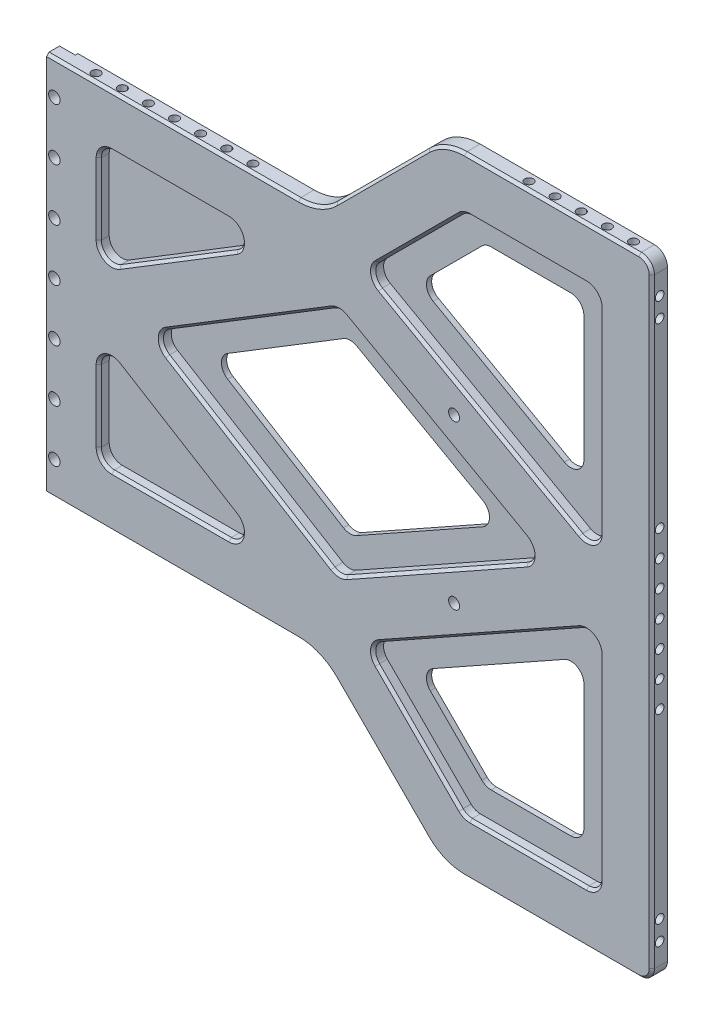
SolidWorks part; units mm, degrees
material "7075-T6 (SN)"
ref_plane "前视基准面" through (0, 0, 0) normal (0, 0, 1) x (1, 0, 0)
ref_plane "上视基准面" through (0, 0, 0) normal (0, 1, 0) x (1, 0, 0)
ref_plane "右视基准面" through (0, 0, 0) normal (1, 0, 0) x (0, 0, -1)
sketch "草图1" plane through (0, 0, 0) normal (0, 0, 1) x (1, 0, 0)
  line L0 (11.5, -73) -> (-13.5, -73) construction
  line L1 (11.5, 73) -> (110.1759, 73)
  line L2 (11.5, 73) -> (11.5, -73)
  line L3 (11.5, -73) -> (110.1759, -73)
  line L5 (387.1759, 0) -> (237.1759, 0) construction
  line L6 (-812.8241, 0) -> (387.1759, 0) construction
  line L7 (237.1759, 120) -> (237.1759, -120)
  line L8 (237.1759, 120) -> (157.1759, 120)
  line L11 (237.1759, -120) -> (157.1759, -120)
  line L12 (157.1759, 120) -> (110.1759, 73)
  line L13 (157.1759, -120) -> (110.1759, -73)
  point P10 (237.1759, 0)
  point P15 (237.1759, 0)
extrude "凸台-拉伸1" add sketch "草图1" against normal blind 1
sketch "草图2" plane through (0, 0, 0) normal (0, 0, 1) x (1, 0, 0)
  line L0 (11.5, 73) -> (5.5, 73)
  line L1 (5.5, 73) -> (5.5, -73)
  line L2 (5.5, -73) -> (11.5, -73)
  line L8 (11.5, 73) -> (11.5, -73)
  line L9 (11.5, -73) -> (110.1759, -73)
  line L10 (110.1759, -73) -> (157.1759, -120)
  line L11 (157.1759, -120) -> (237.1759, -120)
  line L12 (237.1759, -120) -> (237.1759, 120)
  line L13 (237.1759, 120) -> (157.1759, 120)
  line L14 (157.1759, 120) -> (110.1759, 73)
  line L15 (110.1759, 73) -> (11.5, 73)
  line L16 (11.5, 73) -> (11.5, -73) construction
  line L17 (11.5, -73) -> (110.1759, -73)
  line L18 (110.1759, -73) -> (157.1759, -120)
  line L19 (157.1759, -120) -> (237.1759, -120)
  line L20 (237.1759, -120) -> (237.1759, 120)
  line L21 (237.1759, 120) -> (157.1759, 120)
  line L22 (157.1759, 120) -> (110.1759, 73)
  line L23 (110.1759, 73) -> (11.5, 73)
  dimension "D1" = 0
extrude "凸台-拉伸2" add sketch "草图2" along normal blind 5
fillet "圆角1" radius 20 4 edges at (157.1759, 120, 2) (157.1759, -120, 2) (110.1759, -73, 2) (110.1759, 73, 2)
sketch "草图3" plane through (0, 0, 5) normal (0, 0, 1) x (1, 0, 0)
  line L8 (217.1759, 0) -> (117.1989, 56.0448) construction
  line L9 (217.1759, 0) -> (117.1989, -56.0448) construction
  line L11 (25.5, 0) -> (117.1989, 56.0448) construction
  line L12 (25.5, 0) -> (117.1989, -56.0448) construction
  line L13 (237.6263, 0) -> (116.9806, 67.6312)
  line L14 (6.3243, 0) -> (116.9806, 67.6312)
  line L15 (6.3243, 0) -> (116.9806, -67.6312)
  line L16 (217.1759, 100) -> (165.4601, 100)
  line L17 (165.4601, 100) -> (130.1759, 64.7157)
  line L18 (101.8916, 53) -> (25.5, 53)
  line L19 (25.5, 53) -> (25.5, -53)
  line L20 (25.5, -53) -> (101.8916, -53)
  line L21 (130.1759, -64.7157) -> (165.4601, -100)
  line L22 (165.4601, -100) -> (217.1759, -100)
  line L23 (217.1759, -100) -> (217.1759, 100)
  line L24 (217.1759, 100) -> (165.4601, 100)
  line L25 (165.4601, 100) -> (130.1759, 64.7157)
  line L26 (101.8916, 53) -> (25.5, 53)
  line L27 (25.5, 53) -> (25.5, -53)
  line L28 (25.5, -53) -> (101.8916, -53)
  line L29 (130.1759, -64.7157) -> (165.4601, -100)
  line L30 (165.4601, -100) -> (217.1759, -100)
  line L31 (217.1759, -100) -> (217.1759, 100)
  line L32 (237.6263, 0) -> (116.9806, -67.6312)
  line L33 (196.7254, 0) -> (117.4172, 44.4584)
  line L34 (44.6757, 0) -> (117.4172, 44.4584)
  line L35 (44.6757, 0) -> (117.4172, -44.4584)
  line L36 (196.7254, 0) -> (117.4172, -44.4584)
  arc A8 (101.8916, 53) -> (130.1759, 64.7157) centre (101.8916, 93) ccw
  arc A9 (130.1759, -64.7157) -> (101.8916, -53) centre (101.8916, -93) ccw
  arc A10 (101.8916, 53) -> (130.1759, 64.7157) centre (101.8916, 93) ccw
  arc A11 (130.1759, -64.7157) -> (101.8916, -53) centre (101.8916, -93) ccw
  dimension "D2" = 10
  dimension "D1" = 20
  dimension "D3" = 10
extrude "切除-拉伸1" cut sketch "草图3" against normal blind 4 contours L36 L33 L34 L35 | A10 L13 L31 L24 L25 | A11 L29 L30 L31 L32 | L27 L28 L15 | L26 L27 L14
fillet "圆角2" radius 5 18 edges at (165.4601, -100, 3) (217.1759, -100, 3) (217.1759, -11.4641, 3) (127.1113, -61.9522, 3) (217.1759, 11.4641, 3) (165.4601, 100, 3) (127.1113, 61.9522, 3) (117.4172, 44.4584, 3) (44.6757, 0, 3) (117.4172, -44.4584, 3) (196.7254, 0, 3) (25.5, -53, 3) (93.0414, -53, 3) (25.5, -11.7198, 3) (25.5, 53, 3) (25.5, 11.7198, 3) (93.0414, 53, 3) (217.1759, 100, 3)
sketch "草图4" plane through (0, 0, 1) normal (0, 0, 1) x (1, 0, 0)
  line L8 (176.275, 0) -> (117.6355, 32.872)
  line L9 (117.6355, 32.872) -> (63.8513, 0)
  line L10 (63.8513, 0) -> (117.6355, -32.872)
  line L11 (117.6355, -32.872) -> (176.275, 0)
  line L12 (176.275, 0) -> (117.6355, 32.872)
  line L13 (117.6355, 32.872) -> (63.8513, 0)
  line L14 (63.8513, 0) -> (117.6355, -32.872)
  line L15 (117.6355, -32.872) -> (176.275, 0)
  line L19 (143.7124, 64.1101) -> (207.1759, 28.5339)
  line L20 (207.1759, 28.5339) -> (207.1759, 90)
  line L21 (207.1759, 90) -> (169.6023, 90)
  line L22 (169.6023, 90) -> (143.7124, 64.1101)
  line L23 (143.7124, 64.1101) -> (207.1759, 28.5339)
  line L24 (207.1759, 28.5339) -> (207.1759, 90)
  line L25 (207.1759, 90) -> (169.6023, 90)
  line L26 (169.6023, 90) -> (143.7124, 64.1101)
  line L31 (143.7124, -64.1101) -> (169.6023, -90)
  line L32 (169.6023, -90) -> (207.1759, -90)
  line L33 (207.1759, -90) -> (207.1759, -28.5339)
  line L34 (207.1759, -28.5339) -> (143.7124, -64.1101)
  line L35 (143.7124, -64.1101) -> (169.6023, -90)
  line L36 (169.6023, -90) -> (207.1759, -90)
  line L37 (207.1759, -90) -> (207.1759, -28.5339)
  line L38 (207.1759, -28.5339) -> (143.7124, -64.1101)
  dimension "D1" = 10
  dimension "D2" = 10
  dimension "D3" = 10
extrude "切除-拉伸2" cut sketch "草图4" against normal blind 5
fillet "圆角3" radius 5 12 edges at (63.8513, 0, 0) (117.6355, 32.872, 0) (176.275, 0, 0) (117.6355, -32.872, 0) (207.1759, 90, 0) (207.1759, 28.5339, 0) (169.6023, 90, 0) (207.1759, -90, 0) (169.6023, -90, 0) (143.7124, -64.1101, 0) (207.1759, -28.5339, 0) (143.7124, 64.1101, 0)
fillet "圆角4" radius 5 2 edges at (237.1759, 120, 2) (237.1759, -120, 2)
chamfer "倒角1" distance 1 angle 45 36 edges at (26.9645, 51.5355, 5) (25.5, 34.3178, 5) (52.8864, 53, 5) (28.0543, 16.2746, 5) (80.0858, 49.3544, 5) (55.4938, 30.0516, 5) (26.9645, -51.5355, 5) (25.5, -34.3178, 5) (52.8864, -53, 5) (28.0543, -16.2746, 5) (80.0858, -49.3544, 5) (55.4938, -30.0516, 5) (49.2635, 0, 5) (83.2874, 23.5989, 5) (83.2874, -23.5989, 5) (117.4322, 43.6643, 5) (117.4322, -43.6643, 5) (154.4582, 23.694, 5) (154.4582, -23.694, 5) (191.5002, 0, 5) (165.6178, -99.6194, 5) (147.9842, -82.5241, 5) (189.8535, -100, 5) (130.5553, -62.2931, 5) (215.7114, -98.5355, 5) (171.3971, -37.1266, 5) (217.1759, -57.4995, 5) (214.7032, -15.6848, 5) (171.3971, 37.1266, 5) (214.7032, 15.6848, 5) (130.5553, 62.2931, 5) (217.1759, 57.4995, 5) (147.9842, 82.5241, 5) (215.7114, 98.5355, 5) (165.6178, 99.6194, 5) (189.8535, 100, 5)
chamfer "倒角2" distance 1 angle 45 13 edges at (53.6958, 73, 5) (109.5453, 74.5224, 5) (133.6759, 96.5, 5) (53.6958, -73, 5) (157.8065, 118.4776, 5) (109.5453, -74.5224, 5) (198.818, 120, 5) (133.6759, -96.5, 5) (235.7114, 118.5355, 5) (157.8065, -118.4776, 5) (237.1759, 0, 5) (198.818, -120, 5) (235.7114, -118.5355, 5)
sketch "草图5" plane through (0, 0, 5) normal (0, 0, 1) x (1, 0, 0)
  circle A0 centre (8.5, 60) radius 2.2
  circle A1 centre (8.5, 40) radius 2.2
  circle A2 centre (8.5, 20) radius 2.2
  circle A3 centre (8.5, 0) radius 2.2
  circle A4 centre (8.5, -20) radius 2.2
  circle A5 centre (8.5, -40) radius 2.2
  circle A6 centre (8.5, -60) radius 2.2
  point P0 (8.5, 60)
  point P1 (8.5, 40)
  point P3 (8.5, 20)
  point P5 (8.5, 0)
  point P7 (8.5, -20)
  point P9 (8.5, -40)
  point P11 (8.5, -60)
  dimension "D1" = 7
extrude "切除-拉伸3" cut sketch "草图5" against normal through all both and the other way through all
hole_wizard "M4 螺纹孔1" positions "草图7" profile "草图8" tap size "M4" standard "GB"
sketch "草图7" plane through (0, -73, 0) normal (0, -1, 0) x (-1, 0, 0)
  point P0 (-81.5, -2)
  point P3 (-71.5, -2)
  point P6 (-61.5, -2)
  point P9 (-51.5, -2)
  point P12 (-41.5, -2)
  point P15 (-31.5, -2)
  point P18 (-21.5, -2)
sketch "草图8" plane through (81.5, -73, 2) normal (1, 0, 0) x (0, 0, -1)
  line L0 (0, 0) -> (0, 11.0914)
  line L1 (0, 11.0914) -> (1.65, 10.1)
  line L2 (1.65, 10.1) -> (1.65, 0)
  line L5 (1.65, 0) -> (0, 0)
  line L10 (0, 11.0914) -> (-1.65, 10.1) construction
  line L11 (0, -6.35) -> (0, 107.95) construction
  dimension "螺纹孔钻头直径" = 3.3
  dimension "螺纹孔钻头深度" = 10.1
  dimension "导头角度" = 118
cosmetic thread "孔螺蚊线1" parameters "D1"=8, "D2"=4
cosmetic thread "孔螺蚊线2" parameters "D1"=8, "D2"=4
cosmetic thread "孔螺蚊线3" parameters "D1"=8, "D2"=4
cosmetic thread "孔螺蚊线4" parameters "D1"=8, "D2"=4
cosmetic thread "孔螺蚊线5" parameters "D1"=8, "D2"=4
cosmetic thread "孔螺蚊线6" parameters "D1"=8, "D2"=4
cosmetic thread "孔螺蚊线7" parameters "D1"=8, "D2"=4
mirror "镜向1" about plane through (0, 0, 0) normal (0, 1, 0) of "M4 螺纹孔1"
cosmetic thread "孔螺蚊线8" parameters "D1"=8, "D2"=4
cosmetic thread "孔螺蚊线9" parameters "D1"=8, "D2"=4
cosmetic thread "孔螺蚊线10" parameters "D1"=8, "D2"=4
cosmetic thread "孔螺蚊线11" parameters "D1"=8, "D2"=4
cosmetic thread "孔螺蚊线12" parameters "D1"=8, "D2"=4
cosmetic thread "孔螺蚊线13" parameters "D1"=8, "D2"=4
cosmetic thread "孔螺蚊线14" parameters "D1"=8, "D2"=4
hole_wizard "M4 螺纹孔2" positions "草图10" profile "草图11" tap size "M4" standard "GB"
sketch "草图10" plane through (0, -120, 0) normal (0, -1, 0) x (-1, 0, 0)
  point P0 (-227.1759, -2)
  point P3 (-217.1759, -2)
  point P6 (-207.1759, -2)
  point P9 (-197.1759, -2)
  point P12 (-187.1759, -2)
sketch "草图11" plane through (227.1759, -120, 2) normal (1, 0, 0) x (0, 0, -1)
  line L0 (0, 0) -> (0, 11.0914)
  line L1 (0, 11.0914) -> (1.65, 10.1)
  line L2 (1.65, 10.1) -> (1.65, 0)
  line L5 (1.65, 0) -> (0, 0)
  line L10 (0, 11.0914) -> (-1.65, 10.1) construction
  line L11 (0, -6.35) -> (0, 107.95) construction
  dimension "螺纹孔钻头直径" = 3.3
  dimension "螺纹孔钻头深度" = 10.1
  dimension "导头角度" = 118
cosmetic thread "孔螺蚊线15" parameters "D1"=8, "D2"=4
cosmetic thread "孔螺蚊线16" parameters "D1"=8, "D2"=4
cosmetic thread "孔螺蚊线17" parameters "D1"=8, "D2"=4
cosmetic thread "孔螺蚊线18" parameters "D1"=8, "D2"=4
cosmetic thread "孔螺蚊线19" parameters "D1"=8, "D2"=4
mirror "镜向2" about plane through (0, 0, 0) normal (0, 1, 0) of "M4 螺纹孔2"
cosmetic thread "孔螺蚊线20" parameters "D1"=8, "D2"=4
cosmetic thread "孔螺蚊线21" parameters "D1"=8, "D2"=4
cosmetic thread "孔螺蚊线22" parameters "D1"=8, "D2"=4
cosmetic thread "孔螺蚊线23" parameters "D1"=8, "D2"=4
cosmetic thread "孔螺蚊线24" parameters "D1"=8, "D2"=4
hole_wizard "M4 螺纹孔3" positions "草图13" profile "草图14" tap size "M4" standard "GB"
sketch "草图13" plane through (237.1759, 0, 0) normal (1, 0, 0) x (0, 0, -1)
  point P0 (-2, -99.5)
  point P3 (-2, -107)
sketch "草图14" plane through (237.1759, -99.5, 2) normal (0, 1, 0) x (0, 0, -1)
  line L0 (0, 0) -> (0, 11.0914)
  line L1 (0, 11.0914) -> (1.65, 10.1)
  line L2 (1.65, 10.1) -> (1.65, 0)
  line L5 (1.65, 0) -> (0, 0)
  line L10 (0, 11.0914) -> (-1.65, 10.1) construction
  line L11 (0, -6.35) -> (0, 107.95) construction
  dimension "螺纹孔钻头直径" = 3.3
  dimension "螺纹孔钻头深度" = 10.1
  dimension "导头角度" = 118
cosmetic thread "孔螺蚊线26" parameters "D1"=8, "D2"=4
cosmetic thread "孔螺蚊线27" parameters "D1"=8, "D2"=4
mirror "镜向3" about plane through (0, 0, 0) normal (0, 1, 0) of "M4 螺纹孔3"
cosmetic thread "孔螺蚊线28" parameters "D1"=8, "D2"=4
cosmetic thread "孔螺蚊线29" parameters "D1"=8, "D2"=4
sketch "草图15" plane through (0, 0, 5) normal (0, 0, 1) x (1, 0, 0)
  line L0 (151.5, 0) -> (161.5, 0) construction
  line L1 (151.5, 70) -> (151.5, -70) construction
  line L2 (-812.8241, 0) -> (387.1759, 0) construction
  line L3 (133.4954, -36.5917) -> (142.2972, -52.293) construction
  line L4 (189.4341, -5.2337) -> (120.4603, -43.8989) construction
  line L5 (132.5744, -57.7433) -> (209.2419, -14.7652) construction
  line L6 (89.7964, -71.4061) -> (185.9962, -17.4786) construction
  line L7 (161.5, 31.2106) -> (161.5, -31.2106) construction
  point P15 (137.8963, -44.4423)
  point P18 (161.5, 0)
hole_wizard "M5 螺纹孔1" positions "草图16" profile "草图17" tap size "M5" standard "GB"
sketch "草图16" plane through (0, 0, 5) normal (0, 0, 1) x (1, 0, 0)
  point P0 (161.5, 31.2106)
  point P3 (161.5, -31.2106)
sketch "草图17" plane through (161.5, 31.2106, 5) normal (1, 0, 0) x (0, -1, 0)
  line L0 (0, 0) -> (0, 13.6618)
  line L1 (0, 13.6618) -> (2.1, 12.4)
  line L2 (2.1, 12.4) -> (2.1, 0)
  line L5 (2.1, 0) -> (0, 0)
  line L10 (0, 13.6618) -> (-2.1, 12.4) construction
  line L11 (0, -6.35) -> (0, 107.95) construction
  dimension "螺纹孔钻头直径" = 4.2
  dimension "螺纹孔钻头深度" = 12.4
  dimension "导头角度" = 118
cosmetic thread "孔螺蚊线30" parameters "D1"=10, "D2"=5
cosmetic thread "孔螺蚊线31" parameters "D1"=10, "D2"=5
sketch "草图18" plane through (237.1759, 0, 0) normal (1, 0, 0) x (0, 0, -1)
  line L0 (1, 0) -> (-5, 0) construction
  line L1 (1, -115) -> (1, 115) construction
  line L2 (-2, 10) -> (-2, -10) construction
  line L3 (-2, 20) -> (-2, -20) construction
  line L4 (-2, 30) -> (-2, -30) construction
  point P8 (-2, 0)
  point P12 (-2, 0)
  point P15 (-2, 0)
hole_wizard "M4 螺纹孔4" positions "草图19" profile "草图20" tap size "M4" standard "GB"
sketch "草图19" plane through (237.1759, 0, 0) normal (1, 0, 0) x (0, 0, -1)
  line L0 (-2, 10) -> (-2, -10) construction
  point P0 (-2, 30)
  point P3 (-2, 20)
  point P6 (-2, 10)
  point P9 (-2, 0)
  point P13 (-2, -10)
  point P16 (-2, -20)
  point P19 (-2, -30)
sketch "草图20" plane through (237.1759, 30, 2) normal (0, 1, 0) x (0, 0, -1)
  line L0 (0, 0) -> (0, 11.0914)
  line L1 (0, 11.0914) -> (1.65, 10.1)
  line L2 (1.65, 10.1) -> (1.65, 0)
  line L5 (1.65, 0) -> (0, 0)
  line L10 (0, 11.0914) -> (-1.65, 10.1) construction
  line L11 (0, -6.35) -> (0, 107.95) construction
  dimension "螺纹孔钻头直径" = 3.3
  dimension "螺纹孔钻头深度" = 10.1
  dimension "导头角度" = 118
cosmetic thread "孔螺蚊线32" parameters "D1"=8, "D2"=4
cosmetic thread "孔螺蚊线33" parameters "D1"=8, "D2"=4
cosmetic thread "孔螺蚊线34" parameters "D1"=8, "D2"=4
cosmetic thread "孔螺蚊线35" parameters "D1"=8, "D2"=4
cosmetic thread "孔螺蚊线36" parameters "D1"=8, "D2"=4
cosmetic thread "孔螺蚊线37" parameters "D1"=8, "D2"=4
cosmetic thread "孔螺蚊线38" parameters "D1"=8, "D2"=4
